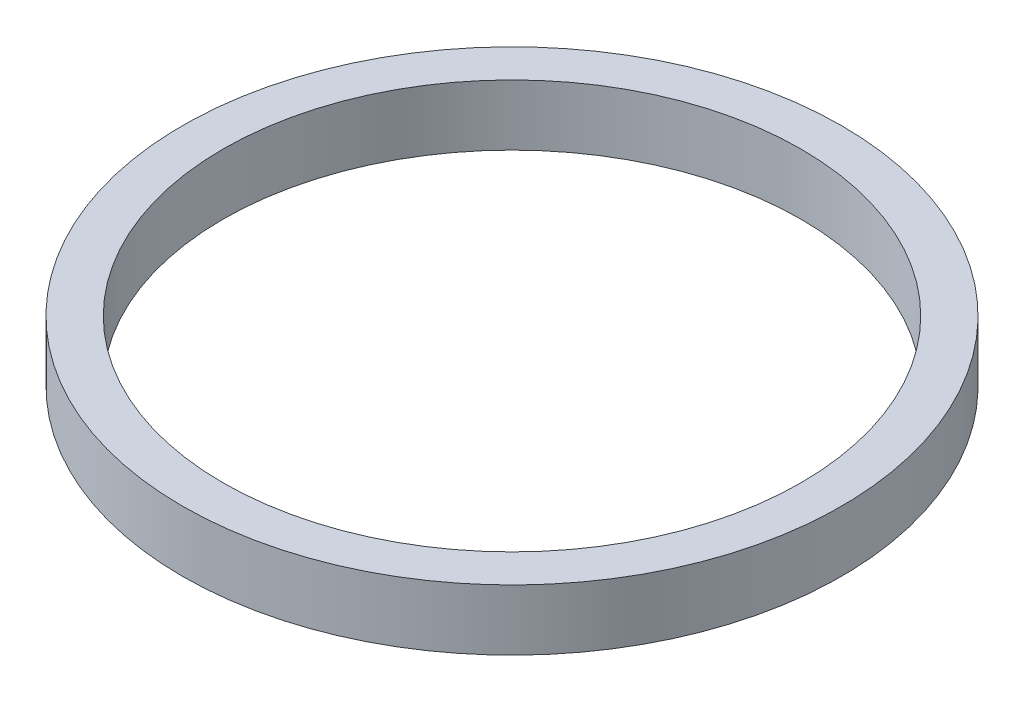
SolidWorks part; units mm, degrees
ref_plane "Front Plane" through (0, 0, 0) normal (0, 0, 1) x (1, 0, 0)
ref_plane "Top Plane" through (0, 0, 0) normal (0, 1, 0) x (1, 0, 0)
ref_plane "Right Plane" through (0, 0, 0) normal (1, 0, 0) x (0, 0, -1)
sketch "Sketch1" plane through (0, 0, 0) normal (0, 1, 0) x (1, 0, 0)
  circle A0 centre (0, 0) radius 16.2625
  circle A1 centre (0, 0) radius 14.2625
  dimension "D1" = 28.525
  dimension "D2" = 2
extrude "Boss-Extrude1" add sketch "Sketch1" along normal blind 3
equation "\"MOTOR_D\"= 28"
equation "\"MOTOR_H\"= 19"
equation "\"MOTHOLE_DIST\"= 35"
equation "\"SHAFT_CENTER_OFF\" = 8"
equation "\"SLIPRING_D\" = 12.4"
equation "\"PITCH_D\"= 52.832"
equation "\"HEX_D\"= 12.7"
equation "\"CENTER_DIST\" = \"PITCH_D\"-\"SHAFT_CENTER_OFF\""
equation "\"BODY_H\"= 70"
equation "\"BODY_W\"= 60"
equation "\"BODY_L\"= 120"
equation "\"BODY_THICK\"= 3"
equation "\"STAND_LOFF\" = 10"
equation "\"STAND_WOFF\" = 5"
equation "\"TAP_HOLE\" = 2.5"
equation "\"SCREW_HOLE\" = 3"
equation "\"HOLE_ANGLE\" = 120"
equation "\"DRVR_HW\" = 31"
equation "\"DRVR_HL\" = 27"
equation "\"BEARING_OD\" = 28.575"
equation "\"BEARING_ID\" = 12.7"
equation "\"BEARING_THICK\" = 7.925"
equation "\"FLANGE_D\" = 31.242"
equation "\"FLANGE_THICK\" = 1.575"
equation "\"COLLAR_OD\" = 20.5"
equation "\"BEARSHAFT_HOLEH\" = 10"
equation "\"STAND_R\" = 3"
equation "\"CB_W\" = 5"
equation "\"CW_DEPTH\" = 1"
equation "\"PIN_SPACING\" = 2.54"
equation "\"PIN_D\" = 1"
equation "\"MBOARD_ZSPACE\" = 7*\"PIN_SPACING\""
equation "\"MBOARD_XSPACE\" = 7*\"PIN_SPACING\""
equation "\"MBOARD_LXSPACE\" = 1*\"PIN_SPACING\""
equation "\"MBOARD_SCREWX\" = 4"
equation "\"MBOARD_ID\" = 15"
equation "\"MBOARD_OD\" = 4 + \"MBOARD_ID\""
equation "\"PCB_THICK\" = 1.5"
equation "\"SHAFTBASE_ID\" = 12.8"
equation "\"SHAFTBASE_OD\" = \"SHAFTBASE_ID\" + 3"
equation "\"SHAFT_D\" = 18"
equation "\"HEXSHAFT_D\" = 12.75"
equation "\"HEXSHAFT_FILLET\" = 2.5"
equation "\"MOUNTHOLE_DIST\" = 4*\"PIN_SPACING\""
equation "\"D1@Sketch1\"=\"BEARING_OD\"-0.05"
